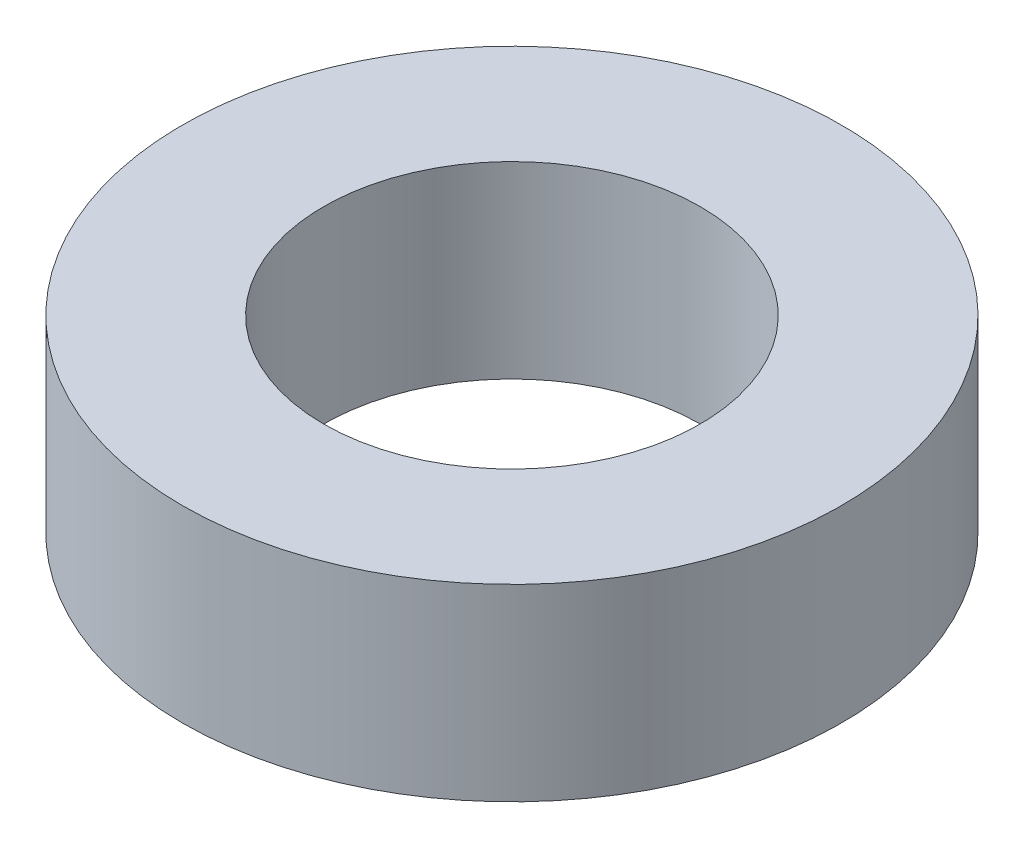
SolidWorks part; units mm, degrees
ref_plane "Front Plane" through (0, 0, 0) normal (0, 0, 1) x (1, 0, 0)
ref_plane "Top Plane" through (0, 0, 0) normal (0, 1, 0) x (1, 0, 0)
ref_plane "Right Plane" through (0, 0, 0) normal (1, 0, 0) x (0, 0, -1)
sketch "Sketch1" plane through (0, 0, 0) normal (0, 1, 0) x (1, 0, 0)
  circle A0 centre (0, 0) radius 11.1125
  dimension "D1" = 22.225
extrude "Boss-Extrude1" add sketch "Sketch1" along normal blind 6.35
sketch "Sketch2" plane through (0, 6.35, 0) normal (0, 1, 0) x (1, 0, 0)
  circle A0 centre (0, 0) radius 6.35
  dimension "D1" = 12.7
extrude "Cut-Extrude1" cut sketch "Sketch2" against normal through all
